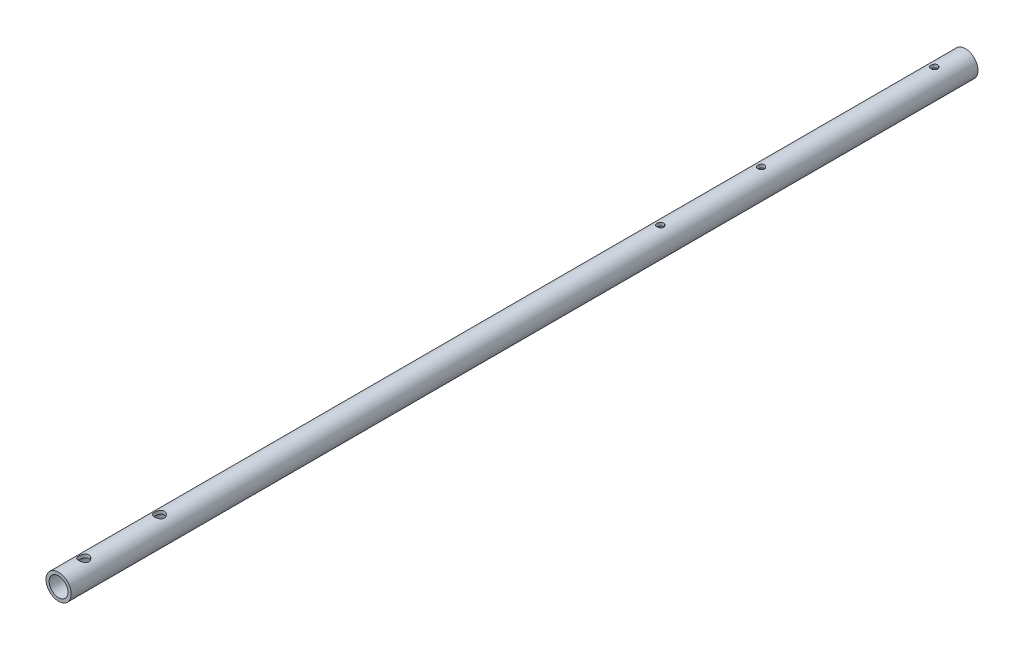
SolidWorks part; units mm, degrees
material "6061-T6 (SS)"
ref_plane "Front" through (0, 0, 0) normal (0, 0, 1) x (1, 0, 0)
ref_plane "Top" through (0, 0, 0) normal (0, 1, 0) x (1, 0, 0)
ref_plane "Right" through (0, 0, 0) normal (1, 0, 0) x (0, 0, -1)
sketch "Sketch1" plane through (0, 0, 0) normal (0, 0, 1) x (1, 0, 0)
  circle A0 centre (0, 0) radius 12.7
  circle A1 centre (0, 0) radius 9.525
  dimension "D1" = 3.175
  dimension "D2" = 25.4
extrude "Boss-Extrude1" add sketch "Sketch1" along normal blind 914.4
ref_plane "Plane1" through (0, -12.7, 0) normal (0, -1, 0) x (-1, 0, 0)
sketch "Sketch2" plane through (0, -12.7, 0) normal (0, 1, 0) x (1, 0, 0)
  line L0 (0, 0) -> (0, -206.121) construction
  line L1 (0, -206.121) -> (0, -812.8) construction
  line L2 (0, -812.8) -> (0, -889) construction
  line L3 (-12.7, -914.4) -> (12.7, -914.4) construction
  point P3 (0, -31.496)
  point P8 (0, -307.721)
  dimension "D1" = 206.121
  dimension "D2" = 31.496
  dimension "D3" = 76.2
  dimension "D4" = 25.4
  dimension "D5" = 101.6
hole_wizard "1/4 Clearance Hole2" positions "Sketch6" profile "Sketch5" hole size "1/4" standard "ANSI Inch" end condition through all
sketch "Sketch6" plane through (0, -12.7, 0) normal (0, -1, 0) x (-1, 0, 0)
  point P0 (0, -206.121)
  point P4 (0, -31.496)
  point P8 (0, -307.721)
sketch "Sketch5" plane through (0, -12.7, 206.121) normal (1, 0, 0) x (0, 0, -1)
  line L0 (0, 0) -> (0, 25.4)
  line L1 (0, 25.4) -> (3.3782, 25.4)
  line L2 (3.3782, 25.4) -> (3.3782, 0)
  line L5 (3.3782, 0) -> (0, 0)
  line L11 (0, -6.35) -> (0, 107.95) construction
  dimension "Thru Hole Dia." = 6.7564
  dimension "Thru Hole Depth" = 25.4
hole_wizard "3/8 Clearance Hole1" positions "Sketch8" profile "Sketch7" hole size "3/8" standard "ANSI Inch" end condition through all
sketch "Sketch8" plane through (0, -12.7, 0) normal (0, -1, 0) x (-1, 0, 0)
  point P0 (0, -889)
  point P3 (0, -812.8)
sketch "Sketch7" plane through (0, -12.7, 889) normal (1, 0, 0) x (0, 0, -1)
  line L0 (0, 0) -> (0, 25.4)
  line L1 (0, 25.4) -> (5.0419, 25.4)
  line L2 (5.0419, 25.4) -> (5.0419, 0)
  line L5 (5.0419, 0) -> (0, 0)
  line L11 (0, -6.35) -> (0, 107.95) construction
  dimension "Thru Hole Dia." = 10.0838
  dimension "Thru Hole Depth" = 25.4
